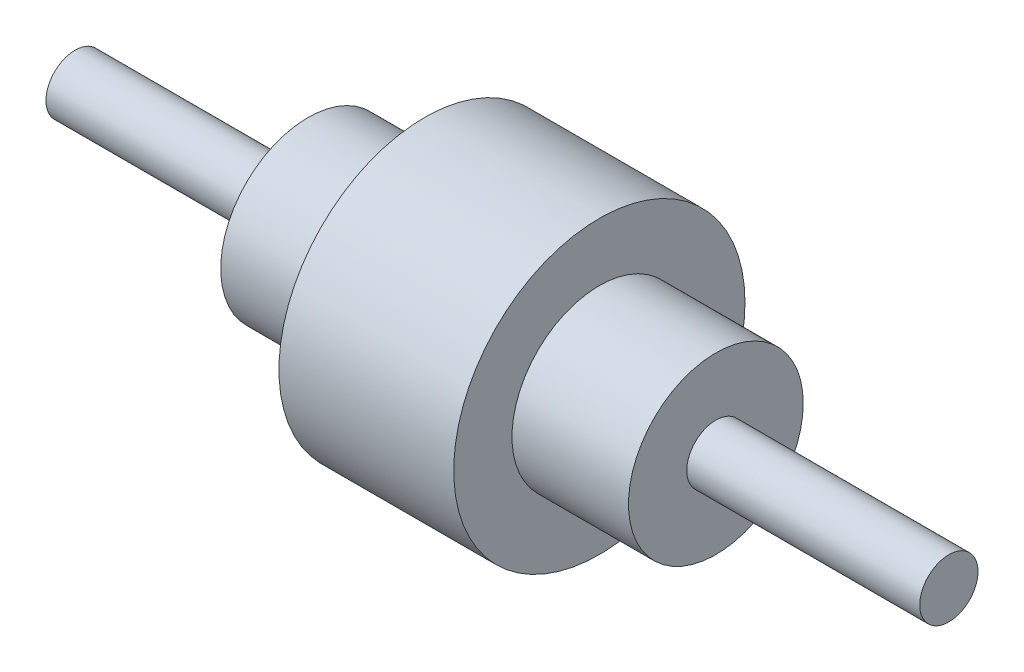
SolidWorks part; units mm, degrees
ref_plane "Alzado" through (0, 0, 0) normal (0, 0, 1) x (1, 0, 0)
ref_plane "Planta" through (0, 0, 0) normal (0, 1, 0) x (1, 0, 0)
ref_plane "Vista lateral" through (0, 0, 0) normal (1, 0, 0) x (0, 0, -1)
sketch "Croquis1" plane through (0, 0, 0) normal (0, 0, 1) x (1, 0, 0)
  line L0 (0, 0) -> (150, 0) construction
  line L1 (150, 0) -> (150, 10)
  line L2 (150, 10) -> (70, 10)
  line L3 (70, 10) -> (70, 30)
  line L4 (70, 30) -> (30, 30)
  line L5 (30, 30) -> (30, 50)
  line L6 (30, 50) -> (-30, 50)
  line L7 (0, 50) -> (0, 0) construction
  line L8 (-150, 0) -> (-150, 10)
  line L9 (-30, 30) -> (-30, 50)
  line L10 (-70, 30) -> (-30, 30)
  line L11 (-70, 10) -> (-70, 30)
  line L12 (-150, 10) -> (-70, 10)
  line L13 (-150, 0) -> (0, 0) construction
  line L14 (150, 0) -> (-150, 0)
  dimension "D1" = 10
  dimension "D3" = 30
  dimension "D4" = 50
  dimension "D2" = 40
  dimension "D5" = 150
  dimension "D6" = 80
revolve "Revolución1" add sketch "Croquis1" angle 360 about L14
equation "\"A\"= 10"
equation "\"D1@Croquis1\"=\"A\""
equation "\"D3@Croquis1\"=\"D1@Croquis1\"*3"
equation "\"D4@Croquis1\"=\"D3@Croquis1\"+(\"D1@Croquis1\"*2)"
equation "\"D5@Croquis1\"=\"D4@Croquis1\"*3"
equation "\"D6@Croquis1\"=\"D2@Croquis1\"*2"
equation "\"D2@Croquis1\"=\"D6@Croquis1\"/2"
